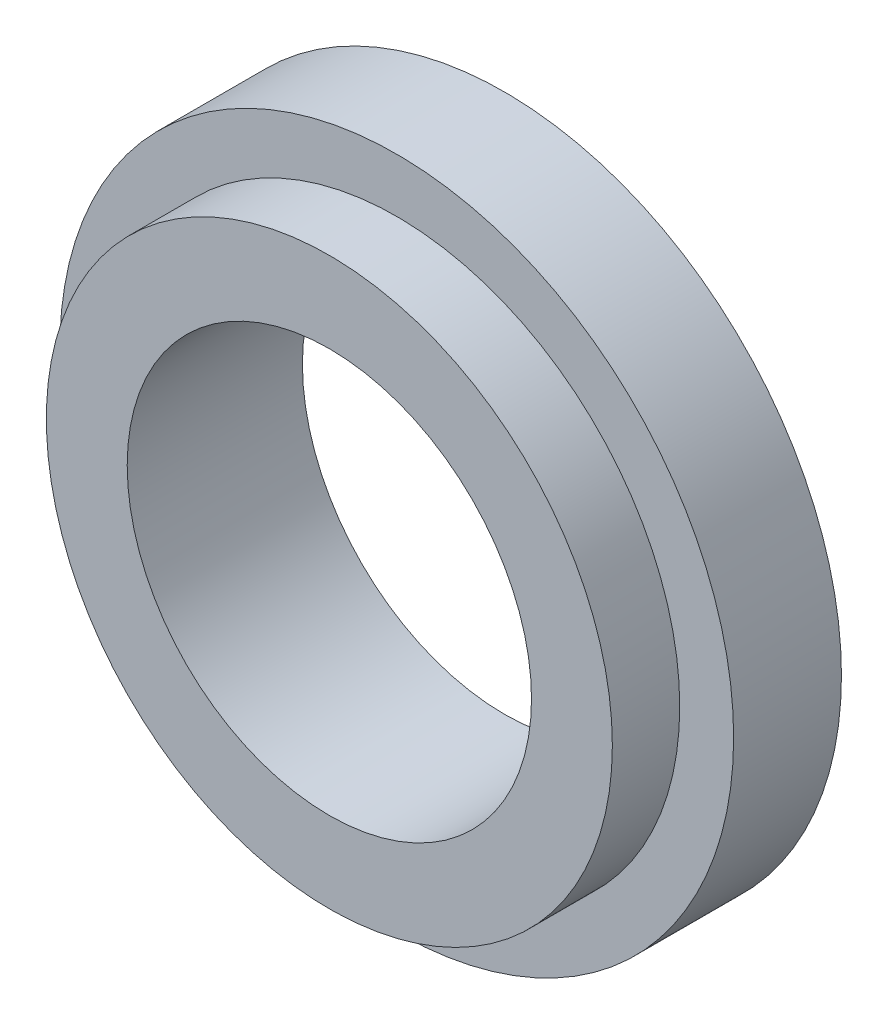
SolidWorks part; units mm, degrees
ref_plane "前视基准面" through (0, 0, 0) normal (0, 0, 1) x (1, 0, 0)
ref_plane "上视基准面" through (0, 0, 0) normal (0, 1, 0) x (1, 0, 0)
ref_plane "右视基准面" through (0, 0, 0) normal (1, 0, 0) x (0, 0, -1)
sketch "草图1" plane through (0, 0, 0) normal (0, 0, 1) x (1, 0, 0)
  circle A0 centre (0, 0) radius 25
extrude "凸台-拉伸1" add sketch "草图1" along normal blind 8
sketch "草图2" plane through (0, 0, 8) normal (0, 0, 1) x (1, 0, 0)
  circle A0 centre (0, 0) radius 21
extrude "凸台-拉伸2" add sketch "草图2" along normal blind 5
sketch "草图3" plane through (0, 0, 13) normal (0, 0, 1) x (1, 0, 0)
  circle A0 centre (0, 0) radius 15
extrude "切除-拉伸1" cut sketch "草图3" against normal blind 13
